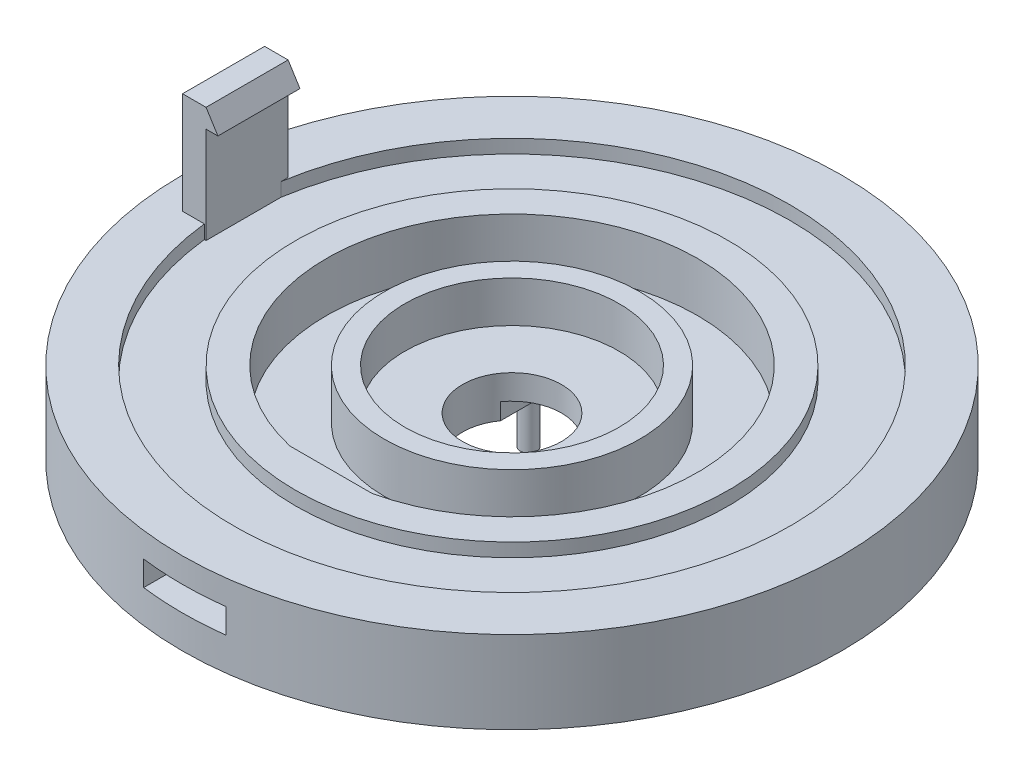
SolidWorks part; units mm, degrees
ref_plane "Front Plane" through (0, 0, 0) normal (0, 0, 1) x (1, 0, 0)
ref_plane "Top Plane" through (0, 0, 0) normal (0, 1, 0) x (1, 0, 0)
ref_plane "Right Plane" through (0, 0, 0) normal (1, 0, 0) x (0, 0, -1)
sketch "Sketch28" plane through (0, 0, 0) normal (0, 1, 0) x (1, 0, 0)
  line L1 (-38.0554, -35.7587) -> (41.9446, -35.7587)
  line L2 (-38.0554, -35.7587) -> (-38.0554, 44.2413)
  line L3 (-38.0554, 44.2413) -> (41.9446, 44.2413)
  line L4 (41.9446, -35.7587) -> (41.9446, 44.2413)
  dimension "D1" = 80
extrude "Boss-Extrude1" add sketch "Sketch28" along normal blind 10
hole_wizard "CBORE for M10 Cheese Head Screw1" positions "Sketch30" profile "Sketch29" counterbore size "M10" standard "AS" end condition through all
sketch "Sketch30" plane through (0, 10, 0) normal (0, 1, 0) x (1, 0, 0)
  point P0 (1.9446, 4.2413)
sketch "Sketch29" plane through (1.9446, 10, -4.2413) normal (1, 0, 0) x (0, 0, 1)
  line L0 (0, 0) -> (0, 10)
  line L1 (0, 10) -> (6, 10)
  line L3 (6, 10) -> (6, 5)
  line L4 (6, 5) -> (13, 5)
  line L5 (13, 5) -> (13, 0)
  line L7 (13, 0) -> (0, 0)
  line L11 (0, -6.35) -> (0, 107.95) construction
  dimension "Thru Hole Dia." = 12
  dimension "Thru Hole Depth" = 10
  dimension "C'Bore Dia." = 26
  dimension "C'Bore Depth" = 5
sketch "Sketch36" plane through (0, 0, 0) normal (0, -1, 0) x (1, 0, 0)
  circle A0 centre (12.4446, -16.7413) radius 1
  circle A1 centre (12.4446, -4.2413) radius 1
  circle A2 centre (-8.5554, -16.7413) radius 1
  circle A3 centre (-8.5554, -4.2413) radius 1
extrude "Boss-Extrude5" add sketch "Sketch36" along normal blind 10
sketch "Sketch37" plane through (0, 10, 0) normal (0, 1, 0) x (1, 0, 0)
  line L0 (1.9446, 44.2413) -> (1.9446, -35.7587) construction
  line L1 (41.9446, 44.2413) -> (-38.0554, 44.2413) construction
  line L2 (-38.0554, -35.7587) -> (41.9446, -35.7587) construction
  line L3 (-38.0554, 4.2413) -> (41.9446, 4.2413) construction
  line L4 (-38.0554, 44.2413) -> (-38.0554, -35.7587) construction
  line L5 (41.9446, -35.7587) -> (41.9446, 44.2413) construction
  circle A0 centre (1.9446, 4.2413) radius 22.5
  circle A1 centre (1.9446, 4.2413) radius 15.5
  dimension "D1" = 31
  dimension "D2" = 45
extrude "Cut-Extrude2" cut sketch "Sketch37" against normal blind 6
sketch "Sketch39" plane through (0, 10, 0) normal (0, 1, 0) x (1, 0, 0)
  line L0 (41.9446, 44.2413) -> (-38.0554, 44.2413) construction
  line L1 (10.8724, 24.8942) -> (-5.6612, 24.8942)
  line L2 (10.8724, 24.8942) -> (10.8724, 44.2413)
  line L3 (10.8724, 44.2413) -> (-5.6612, 44.2413)
  line L4 (-5.6612, 24.8942) -> (-5.6612, 44.2413)
  line L5 (1.9446, -35.7587) -> (6.9446, -35.7587)
  line L6 (-38.0554, -35.7587) -> (41.9446, -35.7587) construction
  line L7 (6.9446, -35.7587) -> (-3.0554, -35.7587)
  line L8 (-3.0554, -35.7587) -> (-3.0554, -17.6961)
  line L9 (-3.0554, -17.6961) -> (6.9446, -17.6961)
  line L10 (6.9446, -17.6961) -> (6.9446, -35.7587)
  circle A0 centre (1.9446, 4.2413) radius 22.5 construction
  circle M5 centre (1.9446, 4.2413) radius 22.5
  line M7 (-38.0554, -35.7587) -> (41.9446, -35.7587)
extrude "Cut-Extrude6" cut sketch "Sketch39" against normal blind 6 contours L10 L8 M5 M7
sketch "Sketch40" plane through (-3.0554, 0, 0) normal (1, 0, 0) x (0, 0, -1)
  line L0 (-35.7587, 4) -> (-35.7587, 10) construction
  line L1 (-35.7587, 7) -> (-17.6961, 7)
  line L2 (-35.7587, 7) -> (-35.7587, 10)
  line L3 (-35.7587, 10) -> (-17.6961, 10)
  line L4 (-17.6961, 7) -> (-17.6961, 10)
extrude "Boss-Extrude7" add sketch "Sketch40" along normal blind 13
sketch "Sketch41" plane through (0, 10, 0) normal (0, 1, 0) x (1, 0, 0)
  circle A0 centre (1.9446, 4.2413) radius 33.75
  circle A1 centre (1.9446, 4.2413) radius 26.25
  dimension "D1" = 67.5
extrude "Cut-Extrude7" cut sketch "Sketch41" against normal blind 1.65
sketch "Sketch42" plane through (0, 0, 0) normal (0, -1, 0) x (1, 0, 0)
  line L0 (-8.5334, -17.7413) -> (-2.9334, -17.7413) construction
  line L1 (12.4446, -17.7413) -> (6.8666, -17.7413) construction
  line L2 (6.8666, -7.591) -> (6.8666, -18.6283)
  line L3 (-2.9334, -18.6283) -> (-2.9334, -7.591)
  line L4 (6.8666, -7.591) -> (-2.9334, -7.591)
  line L5 (6.8666, -18.6283) -> (-2.9334, -18.6283)
  circle A0 centre (12.4446, -16.7413) radius 1 construction
extrude "Cut-Extrude8" cut sketch "Sketch42" against normal blind 2
sketch "Sketch43" plane through (0, 10, 0) normal (0, 1, 0) x (1, 0, 0)
  line L1 (41.9446, 44.2413) -> (-38.0554, 44.2413) construction
  line L2 (1.9446, 44.2413) -> (41.9446, 44.2413)
  line L3 (41.9446, 44.2413) -> (41.9446, -35.7587)
  line L5 (1.9446, 44.2413) -> (-38.0554, 44.2413)
  line L6 (-38.0554, 44.2413) -> (-38.0554, -35.7587)
  line L7 (41.9446, 4.2413) -> (-38.0554, 4.2413) construction
  line L8 (1.9446, -35.7587) -> (41.9446, -35.7587)
  line L9 (1.9446, -35.7587) -> (-38.0554, -35.7587)
  arc A1 (1.9446, -35.7587) -> (1.9446, 44.2413) centre (1.9446, 4.2413) ccw
  arc A2 (1.9446, 44.2413) -> (1.9446, -35.7587) centre (1.9446, 4.2413) ccw
  line M5 (-38.0554, -35.7587) -> (41.9446, -35.7587)
  line M6 (41.9446, -35.7587) -> (41.9446, 44.2413)
  line M7 (41.9446, 44.2413) -> (-38.0554, 44.2413)
  line M8 (-38.0554, 44.2413) -> (-38.0554, -35.7587)
extrude "Cut-Extrude11" cut sketch "Sketch43" against normal blind 20 contours A2 M7 M8 | A2 L6 M5 | A1 M5 M6 | A1 L3 M7
sketch "Sketch45" plane through (0, 8.35, 0) normal (0, 1, 0) x (1, 0, 0)
  line L1 (-34.2365, 10.408) -> (-31.3854, 10.408)
  line L2 (-34.2365, 10.408) -> (-34.2365, 0.4527)
  line L3 (-34.2365, 0.4527) -> (-31.3854, 0.4527)
  line L4 (-31.3854, 10.408) -> (-31.3854, 0.4527)
extrude "Boss-Extrude8" add sketch "Sketch45" along normal blind 14
sketch "Sketch46" plane through (0, 0, -0.4527) normal (0, 0, 1) x (1, 0, 0)
  line L0 (-31.3854, 22.35) -> (-31.3854, 20.0572)
  line L1 (-31.3854, 22.35) -> (-31.3854, 8.35) construction
  line L2 (-31.3854, 20.0572) -> (-29.9445, 20.0572)
  line L3 (-29.9445, 20.0572) -> (-31.3854, 22.35)
extrude "Boss-Extrude9" add sketch "Sketch46" against normal up to vertex
